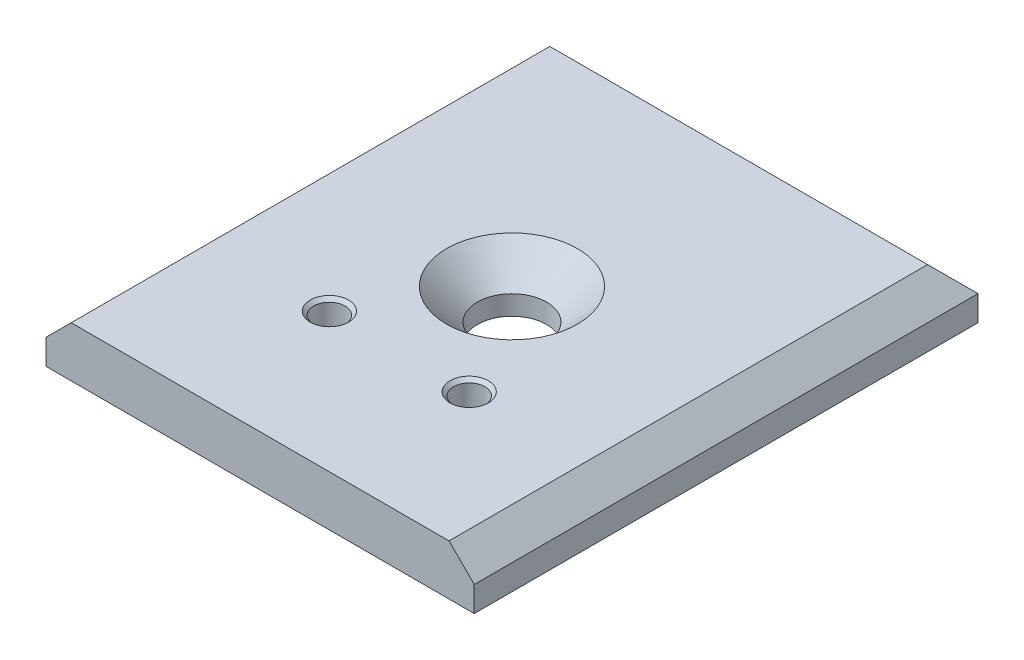
SolidWorks part; units mm, degrees
material "3.1355 (EN-AW 2024)"
ref_plane "Front" through (0, 0, 0) normal (0, 0, 1) x (1, 0, 0)
ref_plane "Top" through (0, 0, 0) normal (0, 1, 0) x (1, 0, 0)
ref_plane "Right" through (0, 0, 0) normal (1, 0, 0) x (0, 0, -1)
sketch "Эскиз1" plane through (0, 0, 0) normal (0, 1, 0) x (1, 0, 0)
  line L1 (-17, 20) -> (17, 20)
  line L2 (-17, 20) -> (-17, -20)
  line L3 (-17, -20) -> (17, -20)
  line L4 (17, 20) -> (17, -20)
  line L5 (-17, 20) -> (17, -20) construction
  line L6 (-17, -20) -> (17, 20) construction
  point P0 (0, 0)
  dimension "D1" = 40
  dimension "D2" = 34
extrude "База" add sketch "Эскиз1" along normal blind 4
hole_wizard "Крепление к профилю 40 - M5" positions "Эскиз2" profile "Эскиз3" countersink size "M5" standard "DIN" end condition through all
sketch "Эскиз2" plane through (0, 4, 0) normal (0, 1, 0) x (-1, 0, 0)
  point P0 (0, 0)
sketch "Эскиз3" plane through (0, 4, 0) normal (1, 0, 0) x (0, 0, 1)
  line L0 (0, 0) -> (0, 4)
  line L1 (0, 4) -> (2.75, 4)
  line L2 (2.75, 4) -> (2.75, 2.45)
  line L3 (2.75, 2.45) -> (5.2, 0)
  line L5 (5.2, 0) -> (0, 0)
  line L6 (-2.75, 2.45) -> (-5.2, 0) construction
  line L11 (0, -6.35) -> (0, 107.95) construction
  dimension "Диаметр сквозного отверстия" = 5.5
  dimension "Глубина сквозного отверстия" = 4
  dimension "Диаметр передней зенковки" = 10.4
  dimension "Угол передней зенковки" = 90
hole_wizard "Крепление датчика" positions "Эскиз6" profile "Эскиз5" tap size "M3" standard "DIN" end condition through all
sketch "Эскиз6" plane through (0, 4, 0) normal (0, 1, 0) x (-1, 0, 0)
  line L0 (5.55, 8.95) -> (0, 8.95) construction
  line L1 (0, 8.95) -> (-5.55, 8.95) construction
  point P0 (5.55, 8.95)
  point P3 (-5.55, 8.95)
  dimension "D1" = 11.1
  dimension "D2" = 8.95
sketch "Эскиз5" plane through (-5.55, 4, 8.95) normal (1, 0, 0) x (0, 0, 1)
  line L0 (0, 0) -> (0, 4)
  line L1 (0, 4) -> (1.25, 4)
  line L2 (1.25, 4) -> (1.25, 0.275)
  line L3 (1.25, 0.275) -> (1.525, 0)
  line L5 (1.525, 0) -> (0, 0)
  line L6 (-1.25, 0.275) -> (-1.525, 0) construction
  line L11 (0, -6.35) -> (0, 107.95) construction
  dimension "Диаметр проходного сверла" = 2.5
  dimension "Глубина проходного сверла" = 4
  dimension "Диаметр передней зенковки" = 3.05
  dimension "Угол передней зенковки" = 90
cosmetic thread "Отверстие резьбы1" parameters "D2"=3
cosmetic thread "Отверстие резьбы2" parameters "D2"=3
chamfer "Фаска1" distance 2 angle 45 4 edges at (0, 4, 20) (17, 4, 0) (0, 4, -20) (-17, 4, 0)
